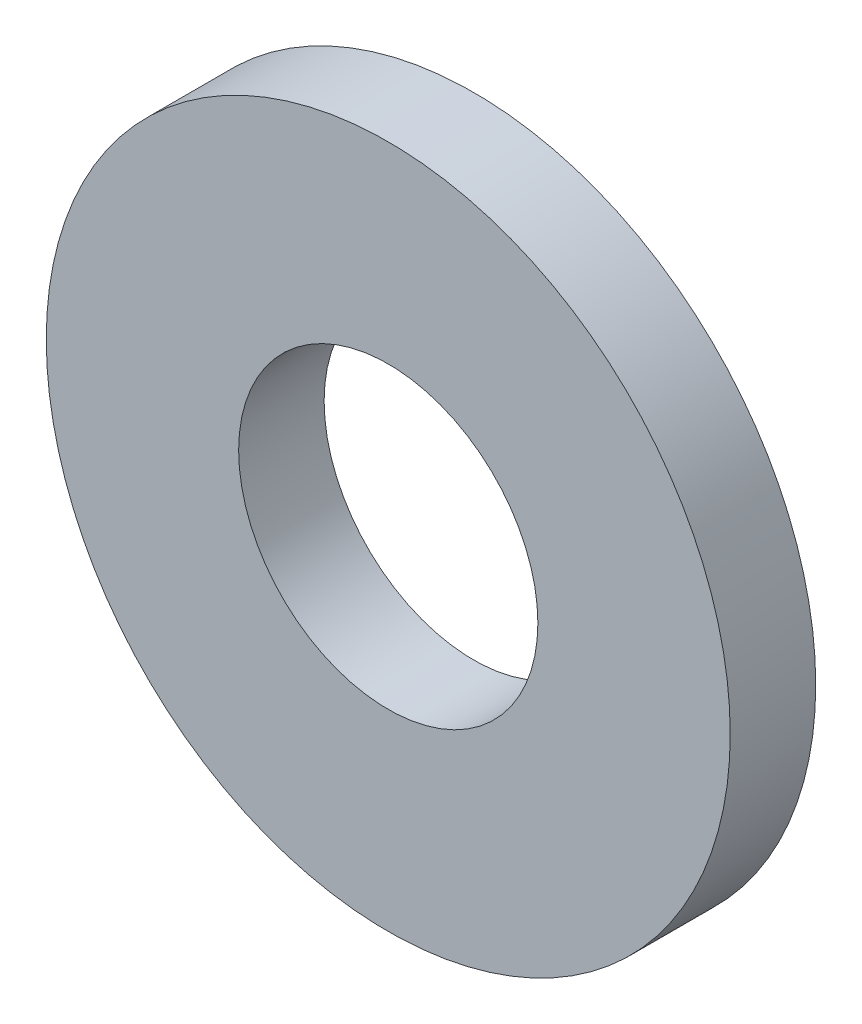
SolidWorks part; units mm, degrees
material "AISI 1020"
ref_plane "Plano frontal" through (0, 0, 0) normal (0, 0, 1) x (1, 0, 0)
ref_plane "Plano superior" through (0, 0, 0) normal (0, 1, 0) x (1, 0, 0)
ref_plane "Plano direito" through (0, 0, 0) normal (1, 0, 0) x (0, 0, -1)
sketch "Esboço1" plane through (0, 0, 0) normal (0, 0, 1) x (1, 0, 0)
  circle A0 centre (0, 0) radius 3.5
  circle A1 centre (0, 0) radius 8
  dimension "D1" = 7
  dimension "D2" = 16
extrude "Ressalto-extrusão1" add sketch "Esboço1" along normal blind 2
